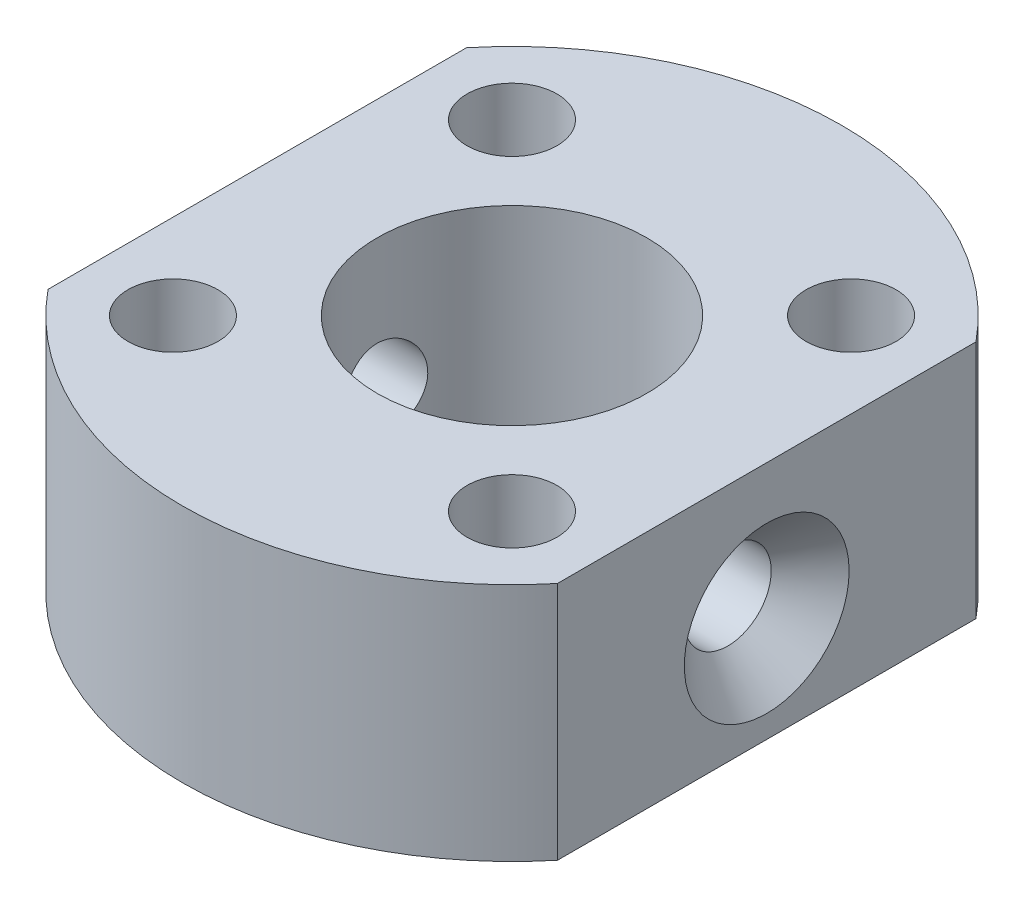
SolidWorks part; units mm, degrees
ref_plane "Front Plane" through (0, 0, 0) normal (0, 0, 1) x (1, 0, 0)
ref_plane "Top Plane" through (0, 0, 0) normal (0, 1, 0) x (1, 0, 0)
ref_plane "Right Plane" through (0, 0, 0) normal (1, 0, 0) x (0, 0, -1)
sketch "Sketch2" plane through (0, 0, 0) normal (0, 1, 0) x (1, 0, 0)
  circle A0 centre (0, 0) radius 11
  dimension "D1" = 22
extrude "Boss-Extrude1" add sketch "Sketch2" along normal blind 8
sketch "Sketch3" plane through (0, 8, 0) normal (0, 1, 0) x (1, 0, 0)
  line L5 (-8.5, 11.5) -> (8.5, 11.5)
  line L6 (-8.5, 11.5) -> (-8.5, -11.5)
  line L7 (-8.5, -11.5) -> (8.5, -11.5)
  line L8 (8.5, 11.5) -> (8.5, -11.5)
  line L9 (0, -11.5) -> (0, 11.5) construction
  line L10 (-8.5, 0) -> (8.5, 0) construction
  point P0 (0, 0)
  dimension "D1" = 8.5
  dimension "D2" = 11.5
extrude "Cut-Extrude1" cut sketch "Sketch3" against normal blind 8 flip side to cut
hole_wizard "Ø9.0 (9) Diameter Hole1" positions "Sketch4" profile "Sketch5" hole size "Ø9.0" standard "ANSI Metric" end condition through all
sketch "Sketch4" plane through (0, 8, 0) normal (0, 1, 0) x (1, 0, 0)
  point P0 (0, 0)
sketch "Sketch5" plane through (0, 8, 0) normal (1, 0, 0) x (0, 0, 1)
  line L0 (0, 0) -> (0, 8)
  line L1 (0, 8) -> (4.5, 8)
  line L2 (4.5, 8) -> (4.5, 0)
  line L5 (4.5, 0) -> (0, 0)
  line L11 (0, -6.35) -> (0, 107.95) construction
  dimension "Thru Hole Dia." = 9
  dimension "Thru Hole Depth" = 8
hole_wizard "CSK for M2.5 Flat Head Machine Screw1" positions "Sketch7" profile "Sketch8" countersink size "M2.5" standard "ANSI Metric"
sketch "Sketch7" plane through (-8.5, 0, 0) normal (-1, 0, 0) x (0, 0, 1)
  line L0 (-6.9821, 8) -> (6.9821, 8) construction
  point P0 (0, 3.5)
  dimension "D1" = 4.5
sketch "Sketch8" plane through (-8.5, 3.5, 0) normal (0, 1, 0) x (0, 0, 1)
  line L0 (0, 0) -> (0, 17)
  line L1 (0, 17) -> (1.45, 17)
  line L2 (1.45, 17) -> (1.45, 1.3)
  line L3 (1.45, 1.3) -> (2.75, 0)
  line L5 (2.75, 0) -> (0, 0)
  line L6 (-1.45, 1.3) -> (-2.75, 0) construction
  line L11 (0, -6.35) -> (0, 107.95) construction
  dimension "Thru Hole Dia." = 2.9
  dimension "Thru Hole Depth" = 17
  dimension "Near C'Sink Dia." = 5.5
  dimension "Near C'Sink Angle" = 90
mirror "Mirror1" about plane through (0, 0, 0) normal (1, 0, 0) of "CSK for M2.5 Flat Head Machine Screw1"
hole_wizard "Ø3.0 (3) Diameter Hole1" positions "Sketch9" profile "Sketch10" hole size "Ø3.0" standard "ANSI Metric"
sketch "Sketch9" plane through (0, 8, 0) normal (0, 1, 0) x (1, 0, 0)
  line L0 (0, 0) -> (-5.6569, 5.6569) construction
  line L2 (-8.5, 6.9821) -> (-8.5, -6.9821) construction
  circle A0 centre (0, 0) radius 8 construction
  point P0 (-5.6569, 5.6569)
  dimension "D1" = 16
  dimension "D2" = 45
sketch "Sketch10" plane through (-5.6569, 8, -5.6569) normal (1, 0, 0) x (0, 0, 1)
  line L0 (0, 0) -> (0, 6.9013)
  line L1 (0, 6.9013) -> (1.5, 6)
  line L2 (1.5, 6) -> (1.5, 0)
  line L5 (1.5, 0) -> (0, 0)
  line L10 (0, 6.9013) -> (-1.5, 6) construction
  line L11 (0, -6.35) -> (0, 107.95) construction
  dimension "Hole Dia." = 3
  dimension "Hole Depth" = 6
  dimension "Drill Angle" = 118
pattern_circular "CirPattern1" count 4 over 360 about axis through (0, 0, 0) along (0, 1, 0) of "Ø3.0 (3) Diameter Hole1"
